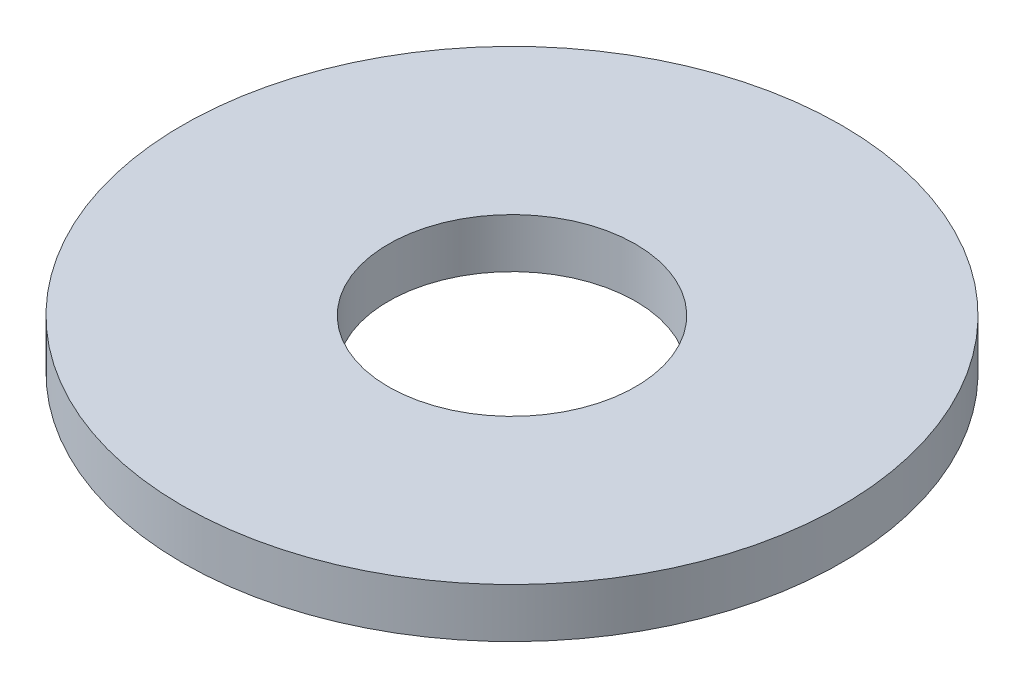
SolidWorks part; units mm, degrees
material "Silicon Rubber"
ref_plane "Front Plane" through (0, 0, 0) normal (0, 0, 1) x (1, 0, 0)
ref_plane "Top Plane" through (0, 0, 0) normal (0, 1, 0) x (1, 0, 0)
ref_plane "Right Plane" through (0, 0, 0) normal (1, 0, 0) x (0, 0, -1)
sketch "Sketch1" plane through (0, 0, 0) normal (0, 1, 0) x (1, 0, 0)
  circle A0 centre (0, 0) radius 7.5
  circle A1 centre (0, 0) radius 20
  dimension "D1" = 15
  dimension "D2" = 40
extrude "Boss-Extrude1" add sketch "Sketch1" along normal blind 3
